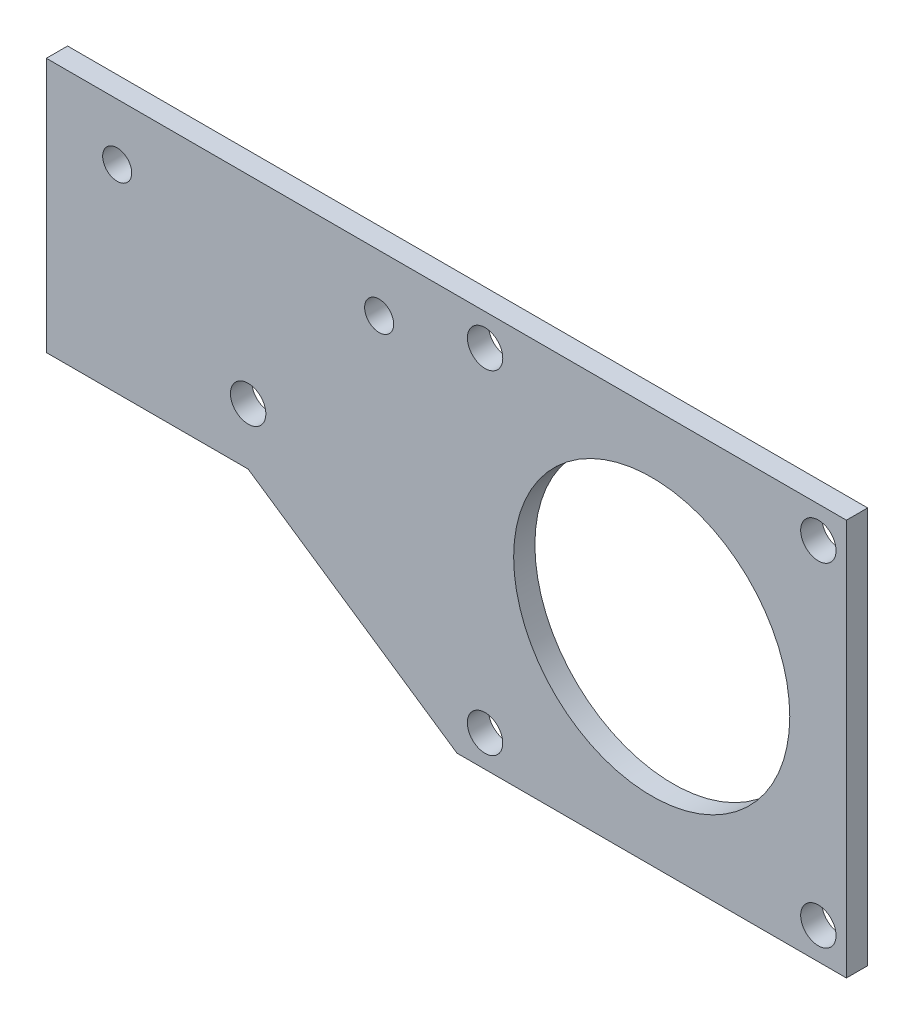
SolidWorks part; units mm, degrees
ref_plane "Front Plane" through (0, 0, 0) normal (0, 0, 1) x (1, 0, 0)
ref_plane "Top Plane" through (0, 0, 0) normal (0, 1, 0) x (1, 0, 0)
ref_plane "Right Plane" through (0, 0, 0) normal (1, 0, 0) x (0, 0, -1)
sketch "Sketch1" plane through (0, 0, 0) normal (0, 0, 1) x (1, 0, 0)
  line L0 (85, 56) -> (85, 0) construction
  line L1 (0, 56) -> (113, 56)
  line L2 (0, 56) -> (0, 0)
  line L3 (0, 0) -> (113, 0)
  line L4 (113, 56) -> (113, 0)
  line L5 (57, 56) -> (57, 0) construction
  line L6 (61.46, -974.9593) -> (61.46, 49025.0407) construction
  line L7 (108.54, -973.2179) -> (108.54, 49026.7821) construction
  line L8 (-925.8289, 51.54) -> (49074.1711, 51.54) construction
  line L9 (-926.3265, 4.46) -> (49073.6735, 4.46) construction
  circle A1 centre (28.5, 28) radius 2.5
  dimension "D5" = 5
  dimension "D1" = 113
  dimension "D2" = 56
  dimension "D3" = 28
  dimension "D7" = 56
  dimension "D8" = 4.46
  dimension "D9" = 4.46
  dimension "D10" = 4.46
  dimension "D11" = 4.46
extrude "Boss-Extrude1" add sketch "Sketch1" along normal blind 3
sketch "Sketch2" plane through (0, 0, 3) normal (0, 0, 1) x (1, 0, 0)
  line L0 (0, 28) -> (113, 28) construction
  line L1 (0, 56) -> (0, 0) construction
  line L2 (113, 0) -> (113, 56) construction
  line L3 (58, 0) -> (28.5, 20)
  line L4 (0, 20) -> (0, 28)
  line L5 (28.5, 20) -> (0, 20)
  line L7 (28.5, 36) -> (28.5, 20) construction
  line L8 (0, 0) -> (113, 0) construction
  line L9 (58, 0) -> (11.4799, -13.7322)
  line L10 (11.4799, -13.7322) -> (-30.0355, 6.5289)
  line L11 (-30.0355, 6.5289) -> (0, 28)
  point P19 (28.5, 28)
  point P23 (20.5, 28)
  dimension "D1" = 55
  dimension "D2" = 8
extrude "Cut-Extrude1" cut sketch "Sketch2" against normal blind 3
sketch "Sketch3" plane through (0, 0, 0) normal (0, 0, -1) x (-1, 0, 0)
  circle A0 centre (-47.0012, 47.9994) radius 2.05
  circle A1 centre (-10.0012, 48.0016) radius 2.05
  circle A2 centre (-10.0012, 48.0016) radius 2.05 construction
  circle A3 centre (-47.0012, 47.9994) radius 2.05 construction
extrude "Cut-Extrude2" cut sketch "Sketch3" against normal blind 10
sketch "Sketch5" plane through (0, 0, 3) normal (0, 0, 1) x (1, 0, 0)
  circle A0 centre (85.5, 27.9971) radius 19.5
  circle A1 centre (109.04, 51.5343) radius 2.5
  circle A2 centre (61.9628, 51.5371) radius 2.5
  circle A3 centre (109.0372, 4.4571) radius 2.5
  circle A4 centre (61.96, 4.4599) radius 2.5
  dimension "D1" = 39
  dimension "D2" = 5
extrude "Cut-Extrude4" cut sketch "Sketch5" against normal blind 10
